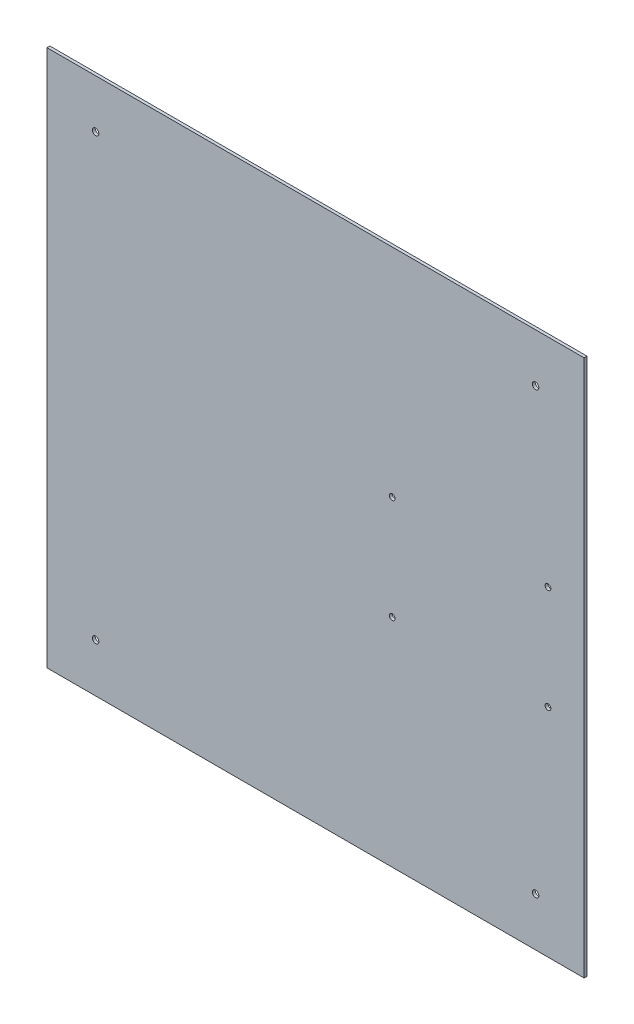
SolidWorks part; units mm, degrees
ref_plane "Front Plane" through (0, 0, 0) normal (0, 0, 1) x (1, 0, 0)
ref_plane "Top Plane" through (0, 0, 0) normal (0, 1, 0) x (1, 0, 0)
ref_plane "Right Plane" through (0, 0, 0) normal (1, 0, 0) x (0, 0, -1)
sketch "Sketch1" plane through (0, 0, 0) normal (0, 0, 1) x (1, 0, 0)
  line L0 (-185, 185) -> (-151.5362, 151.5362) construction
  line L1 (-185, 185) -> (185, 185)
  line L2 (-185, 185) -> (-185, -185)
  line L3 (-185, -185) -> (185, -185)
  line L4 (185, 185) -> (185, -185)
  line L5 (-185, 185) -> (185, -185) construction
  line L6 (-185, -185) -> (185, 185) construction
  line L7 (185, 185) -> (151.5362, 151.5362) construction
  line L8 (185, -185) -> (151.5362, -151.5362) construction
  line L9 (-185, -185) -> (-151.5362, -151.5362) construction
  line L10 (-231.7957, 0) -> (311.5305, 0) construction
  line L12 (166.4428, -40) -> (46.4428, -40)
  line L13 (166.4428, -40) -> (166.4428, 40)
  line L14 (166.4428, 40) -> (46.4428, 40)
  line L15 (46.4428, -40) -> (46.4428, 40)
  line L16 (166.4428, -40) -> (46.4428, 40) construction
  line L17 (166.4428, 40) -> (46.4428, -40) construction
  circle A0 centre (-151.5362, 151.5362) radius 2.25
  circle A1 centre (151.5362, 151.5362) radius 2.25
  circle A2 centre (151.5362, -151.5362) radius 2.25
  circle A3 centre (-151.5362, -151.5362) radius 2.25
  circle A4 centre (52.7771, 35.7771) radius 2
  circle A5 centre (52.7803, -35.775) radius 2
  circle A6 centre (160.1053, 35.775) radius 2
  circle A7 centre (160.1053, -35.775) radius 2
  point P0 (0, 0)
  point P16 (106.4428, 0)
  dimension "D4" = 4.5
  dimension "D6" = 4.5
  dimension "D8" = 4.5
  dimension "D10" = 4.5
  dimension "D13" = 107.3282
  dimension "D15" = 4
  dimension "D16" = 4
  dimension "D17" = 4
  dimension "D18" = 4
  dimension "D1" = 370
  dimension "D2" = 370
  dimension "D3" = 47.325
  dimension "D5" = 47.325
  dimension "D7" = 47.325
  dimension "D9" = 47.325
  dimension "D11" = 120
  dimension "D12" = 80
  dimension "D14" = 71.5521
extrude "Boss-Extrude2" add sketch "Sketch1" along normal blind 2 contours L15 L12 L13 L14 A7 A6 A5 A4 | L4 L1 L2 L3 A3 A2 A1 A0 L12 L15 L14 L13
